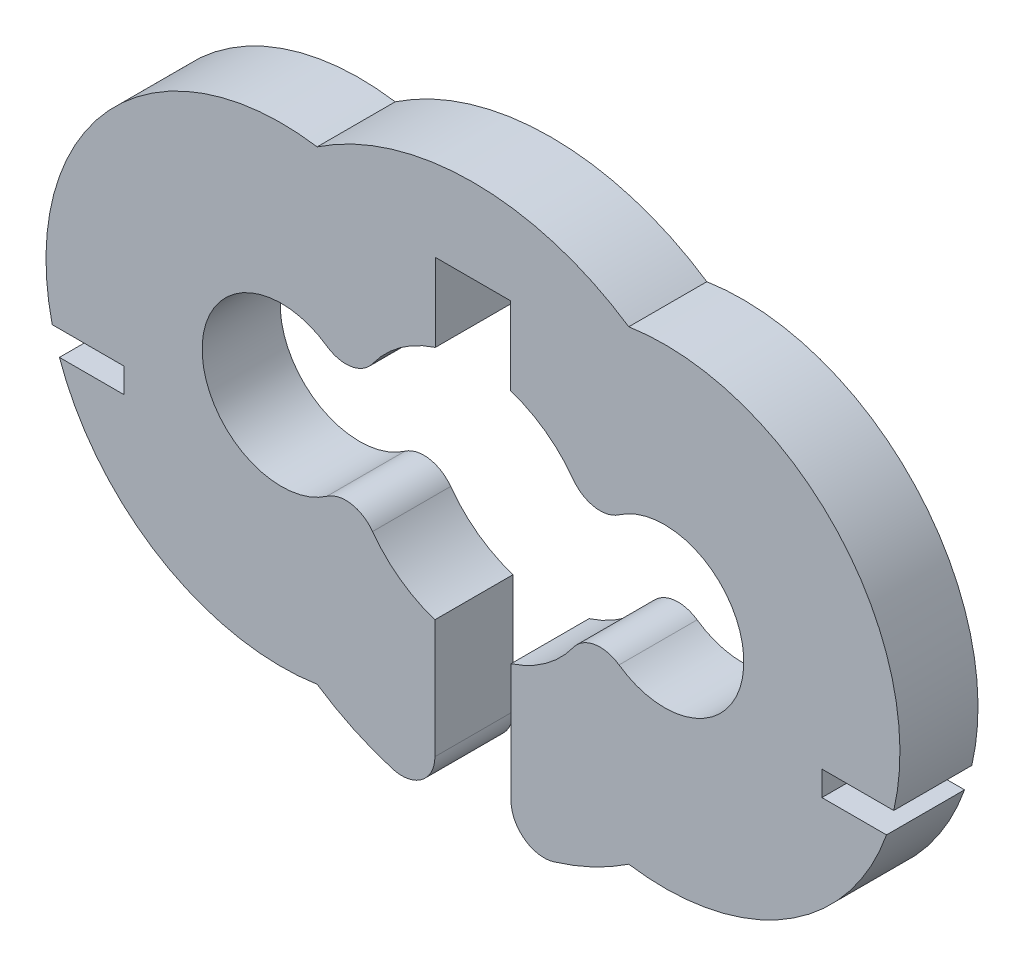
SolidWorks part; units mm, degrees
material "Acrylic (Medium-high impact)"
ref_plane "Front Plane" through (0, 0, 0) normal (0, 0, 1) x (1, 0, 0)
ref_plane "Top Plane" through (0, 0, 0) normal (0, 1, 0) x (1, 0, 0)
ref_plane "Right Plane" through (0, 0, 0) normal (1, 0, 0) x (0, 0, -1)
sketch "스케치1" plane through (0, 0, 0) normal (0, 0, 1) x (1, 0, 0)
  line L0 (0, 10.85) -> (0, 0) construction
  line L5 (-4.59, 1.27) -> (-4.59, -1.27) construction
  line L6 (-1.4475, 7.5372) -> (1.4475, 7.5372)
  line L7 (0, 0) -> (0, -7.5975) construction
  line L8 (-1.4625, -10.6627) -> (1.4625, -10.6627) construction
  line L9 (-1.4625, -10.6627) -> (-1.4625, -4.5324)
  line L10 (-1.4625, -4.5324) -> (1.4625, -4.5324) construction
  line L11 (1.4625, -10.6627) -> (1.4625, -4.5324)
  line L12 (-1.4625, -10.6627) -> (1.4625, -4.5324) construction
  line L13 (-1.4625, -4.5324) -> (1.4625, -10.6627) construction
  line L14 (-1.4475, 7.5372) -> (-1.4475, 4.5372)
  line L15 (-1.4475, 4.5372) -> (1.4475, 4.5372) construction
  line L16 (1.4475, 7.5372) -> (1.4475, 4.5372)
  line L17 (-1.4475, 7.5372) -> (1.4475, 4.5372) construction
  line L18 (-1.4475, 4.5372) -> (1.4475, 7.5372) construction
  line L19 (-4.59, 0) -> (0, 0) construction
  circle A0 centre (0, 0) radius 10.7625 construction
  circle A1 centre (0, 0) radius 4.7625 construction
  arc A2 (-1.4625, -10.6627) -> (1.4625, -10.6627) centre (0, 0) cw construction
  arc A3 (1.4625, -4.5324) -> (1.4475, 4.5372) centre (0, 0) ccw construction
  arc A4 (-1.4475, 4.5372) -> (-1.4625, -4.5324) centre (0, 0) ccw construction
  arc A5 (-5.9876, 8.9432) -> (-5.9876, -8.9432) centre (-7.3609, 0) ccw
  arc A6 (-4.59, 1.27) -> (-4.59, -1.27) centre (-7.3609, 0) ccw construction
  arc A7 (-4.59, 1.27) -> (-4.59, -1.27) centre (-7.3609, 0) ccw
  arc A8 (-4.59, 1.27) -> (-1.4475, 4.5372) centre (0, 0) cw
  arc A9 (-4.59, -1.27) -> (-1.4625, -4.5324) centre (0, 0) ccw
  arc A10 (-5.9876, -8.9432) -> (-1.4625, -10.6627) centre (0, 0) ccw
  arc A11 (4.59, 1.27) -> (1.4475, 4.5372) centre (0, 0) ccw
  arc A12 (4.59, -1.27) -> (1.4625, -4.5324) centre (0, 0) cw
  arc A13 (4.59, 1.27) -> (4.59, -1.27) centre (7.3609, 0) cw
  arc A14 (5.9876, -8.9432) -> (1.4625, -10.6627) centre (0, 0) cw
  arc A15 (5.9876, 8.9432) -> (5.9876, -8.9432) centre (7.3609, 0) cw
  arc A16 (-5.9876, 8.9432) -> (5.9876, 8.9432) centre (0, 0) cw
  point P2 (0, 10.85)
  point P5 (0, 6.0372)
  point P10 (0, -7.5975)
  dimension "D1" = 6
  dimension "D2" = 9.525
  dimension "D6" = 6
  dimension "D7" = 3.048
  dimension "D3" = 2.895
  dimension "D4" = 3
  dimension "D5" = 2.925
  dimension "D8" = 2.54
extrude "보스-돌출1" add sketch "스케치1" along normal blind 3
sketch "스케치2" plane through (0, 0, 3) normal (0, 0, 1) x (1, 0, 0)
  line L0 (0, 0) -> (-10.4089, 0) construction
  line L1 (-16.4089, -4.54) -> (-13.4089, -4.54) construction
  line L2 (-16.4089, -4.54) -> (-16.4089, -0.54) construction
  line L3 (-16.4089, -0.54) -> (-13.4089, -0.54) construction
  line L4 (-13.4089, -4.54) -> (-13.4089, -0.54) construction
  line L5 (-16.4089, -4.54) -> (-13.4089, -0.54) construction
  line L6 (-16.4089, -0.54) -> (-13.4089, -4.54) construction
  line L7 (0, 0) -> (0, 10.7625) construction
  line L8 (16.4089, -0.54) -> (13.4089, -0.54) construction
  line L9 (16.4089, -4.54) -> (16.4089, -0.54) construction
  line L10 (16.4089, -4.54) -> (13.4089, -4.54) construction
  line L11 (13.4089, -4.54) -> (13.4089, -0.54) construction
  line L12 (13.4089, -3.59) -> (16.4089, -3.59) construction
  line L13 (-16.4089, -0.54) -> (-13.4089, -0.54) construction
  line L14 (-16.4089, -0.54) -> (-16.4089, -1.49) construction
  line L15 (-16.4089, -1.49) -> (-13.4089, -1.49) construction
  line L16 (-13.4089, -0.54) -> (-13.4089, -1.49) construction
  line L17 (-16.4089, -0.54) -> (-13.4089, -1.49) construction
  line L18 (-16.4089, -1.49) -> (-13.4089, -0.54) construction
  line L19 (-13.4089, -4.54) -> (-16.4089, -4.54) construction
  line L20 (-13.4089, -4.54) -> (-13.4089, -3.59) construction
  line L21 (-13.4089, -3.59) -> (-16.4089, -3.59) construction
  line L22 (-16.4089, -4.54) -> (-16.4089, -3.59) construction
  line L23 (-13.4089, -4.54) -> (-16.4089, -3.59) construction
  line L24 (-13.4089, -3.59) -> (-16.4089, -4.54) construction
  line L25 (16.4089, -4.54) -> (16.4089, -3.59) construction
  line L26 (13.4089, -4.54) -> (16.4089, -4.54) construction
  line L27 (13.4089, -4.54) -> (13.4089, -3.59) construction
  line L28 (16.4089, -1.49) -> (13.4089, -1.49) construction
  line L29 (13.4089, -0.54) -> (13.4089, -1.49) construction
  line L30 (16.4089, -0.54) -> (13.4089, -0.54) construction
  line L31 (16.4089, -0.54) -> (16.4089, -1.49) construction
  line L32 (16.4089, -2.065) -> (13.4089, -2.065)
  line L33 (-16.4089, -3.015) -> (-13.4089, -3.015)
  line L34 (-16.4089, -3.015) -> (-16.4089, -2.065)
  line L35 (-16.4089, -2.065) -> (-13.4089, -2.065)
  line L36 (-13.4089, -3.015) -> (-13.4089, -2.065)
  line L37 (-16.4089, -3.015) -> (-13.4089, -2.065) construction
  line L38 (-16.4089, -2.065) -> (-13.4089, -3.015) construction
  line L39 (13.4089, -3.015) -> (13.4089, -2.065)
  line L40 (16.4089, -3.015) -> (13.4089, -3.015)
  line L41 (16.4089, -3.015) -> (16.4089, -2.065)
  arc A0 (-5.9876, 8.9432) -> (-5.9876, -8.9432) centre (-7.3609, 0) ccw construction
  arc A1 (5.9876, 8.9432) -> (-5.9876, 8.9432) centre (0, 0) ccw construction
  arc A2 (-4.59, 1.27) -> (-4.59, -1.27) centre (-7.3609, 0) ccw construction
  point P0 (-14.9089, -2.54)
  point P25 (-14.9089, -1.015)
  point P29 (-14.9089, -4.065)
  point P34 (-14.9089, -2.54)
  dimension "D1" = 3
  dimension "D2" = 2.54
  dimension "D3" = 4
  dimension "D4" = 0.95
  dimension "D5" = 0.95
extrude "컷-돌출1" cut sketch "스케치2" against normal up to surface (3 mm away) up to face at (0, -0.3082, 0)
fillet "필렛1" radius 1.27 6 edges at (-1.4625, -10.6627, 1.5) (1.4625, -10.6627, 1.5) (4.59, -1.27, 1.5) (-4.59, -1.27, 1.5) (-4.59, 1.27, 1.5) (4.59, 1.27, 1.5)
